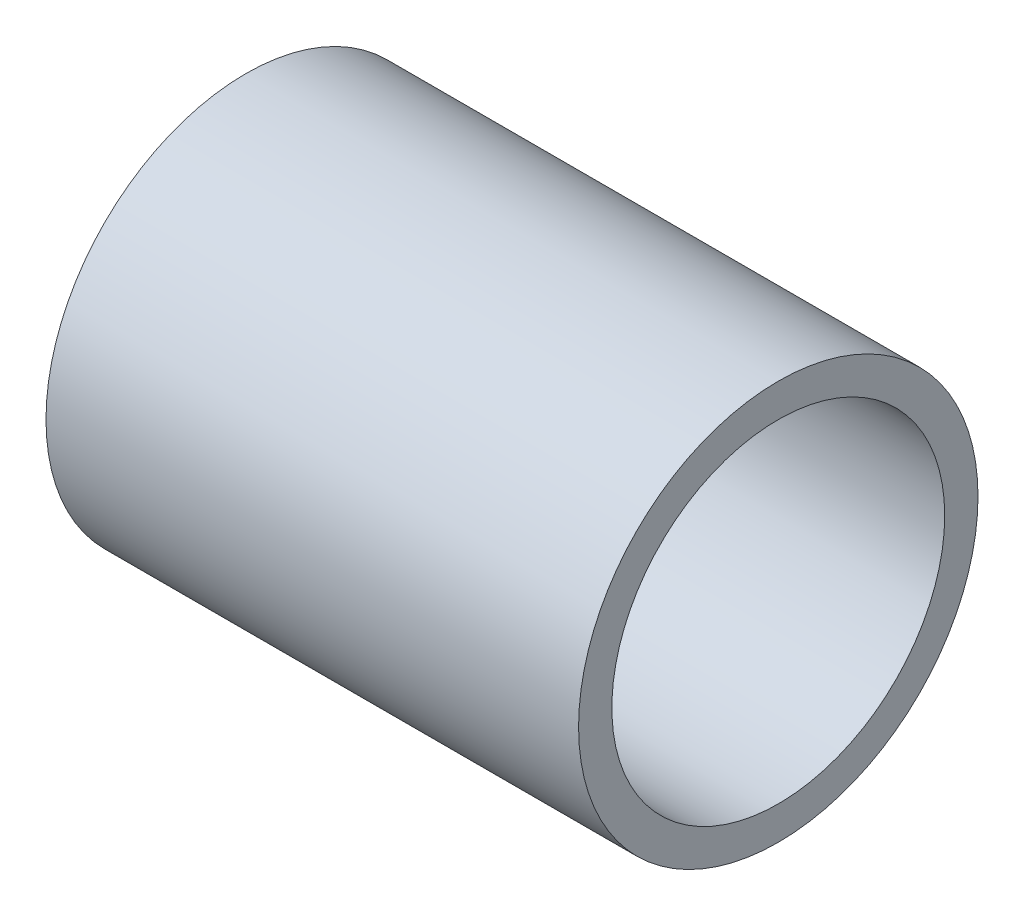
SolidWorks part; units mm, degrees
material "Aluminum Bronze"
ref_plane "Front Plane" through (0, 0, 0) normal (0, 0, 1) x (1, 0, 0)
ref_plane "Top Plane" through (0, 0, 0) normal (0, 1, 0) x (1, 0, 0)
ref_plane "Right Plane" through (0, 0, 0) normal (1, 0, 0) x (0, 0, -1)
sketch "Sketch1" plane through (0, 0, 0) normal (0, 0, 1) x (1, 0, 0)
  line L0 (12.597, 0) -> (-12.597, 0) construction
  line L1 (12.7, -9.525) -> (12.7, -7.9375) construction
  line L2 (-12.7, 9.525) -> (12.7, 9.525)
  line L3 (-12.7, 9.525) -> (-12.7, 7.9375)
  line L4 (-12.7, 7.9375) -> (12.7, 7.9375)
  line L5 (12.7, 9.525) -> (12.7, 7.9375)
  line L6 (-12.7, -7.9375) -> (12.7, -7.9375) construction
  line L7 (-12.7, -9.525) -> (-12.7, -7.9375) construction
  line L8 (-12.7, -9.525) -> (12.7, -9.525) construction
  line L9 (0, 9.525) -> (0, -9.525) construction
  dimension "D1" = 25.4
  dimension "D2" = 19.05
  dimension "D3" = 15.875
  dimension "D4" = 15.875
revolve "Revolve1" add sketch "Sketch1" angle 360 about L0
